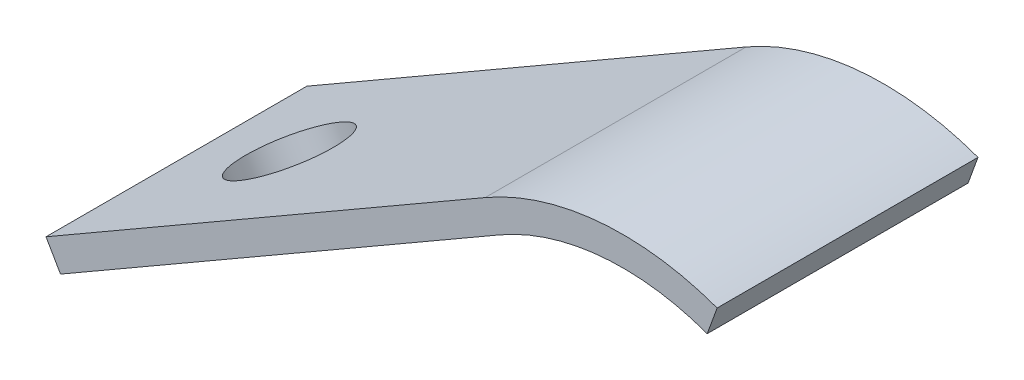
SolidWorks part; units mm, degrees
material "AISI 1010 钢，热轧条材"
ref_plane "前视基准面" through (0, 0, 0) normal (0, 0, 1) x (1, 0, 0)
ref_plane "上视基准面" through (0, 0, 0) normal (0, 1, 0) x (1, 0, 0)
ref_plane "右视基准面" through (0, 0, 0) normal (1, 0, 0) x (0, 0, -1)
sketch "草图1" plane through (0, 0, 0) normal (0, 0, 1) x (1, 0, 0)
  line L0 (-38.8109, -2.7776) -> (-8.5, 14.7224)
  line L1 (0, 0) -> (8.1193, 22.3076) construction
  line L2 (0, 0) -> (0, 20.26) construction
  line L3 (-39.8109, -1.0455) -> (-9.5, 16.4545)
  line L4 (-39.8109, -1.0455) -> (-38.8109, -2.7776)
  line L5 (6.4984, 17.8542) -> (5.8143, 15.9748)
  arc A0 (5.8143, 15.9748) -> (-8.5, 14.7224) centre (0, 0) ccw
  arc A1 (6.4984, 17.8542) -> (-9.5, 16.4545) centre (0, 0) ccw
  dimension "D1" = 34
  dimension "D2" = 35
  dimension "D3" = 20
  dimension "D4" = 2
  dimension "D5" = 60
extrude "凸台-拉伸1" add sketch "草图1" along normal mid plane 18
sketch "草图2" plane through (-9.5, 16.4545, 0) normal (-0.5, 0.866, 0) x (0.866, 0.5, 0)
  line L0 (-35, 0) -> (-17.822, 0) construction
  line L1 (-35, -9) -> (-35, 9) construction
  circle A0 centre (-26, 0) radius 3.5
  dimension "D1" = 7
  dimension "D2" = 9
extrude "切除-拉伸1" cut sketch "草图2" against normal blind 18
